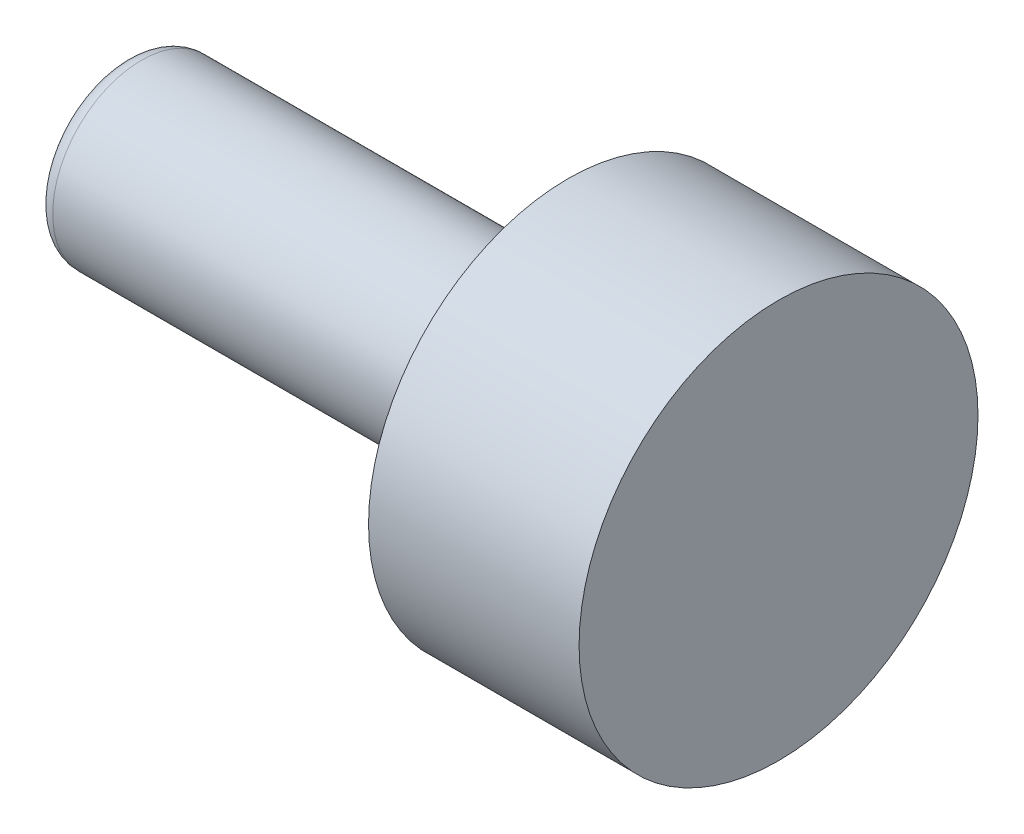
SolidWorks part; units mm, degrees
ref_plane "Front Plane" through (0, 0, 0) normal (0, 0, 1) x (1, 0, 0)
ref_plane "Top Plane" through (0, 0, 0) normal (0, 1, 0) x (1, 0, 0)
ref_plane "Right Plane" through (0, 0, 0) normal (1, 0, 0) x (0, 0, -1)
sketch "Sketch3" plane through (0, 0, 0) normal (1, 0, 0) x (0, 0, -1)
  circle A0 centre (0, 0) radius 16
extrude "Boss-Extrude1" add sketch "Sketch3" along normal blind 80
sketch "Sketch4" plane through (80, 0, 0) normal (1, 0, 0) x (0, 0, -1)
  circle A0 centre (0, 0) radius 36
extrude "Boss-Extrude2" add sketch "Sketch4" along normal blind 38
fillet "Fillet1" radius 3 2 edges at (80, 0, -16) (0, 0, -16)
